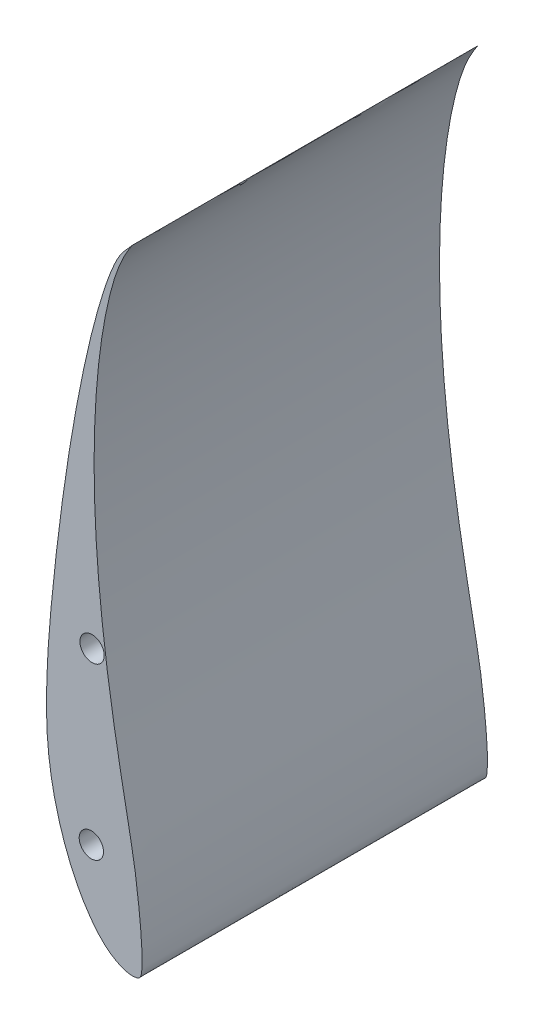
SolidWorks part; units mm, degrees
ref_plane "Front Plane" through (0, 0, 0) normal (0, 0, 1) x (1, 0, 0)
ref_plane "Top Plane" through (0, 0, 0) normal (0, 1, 0) x (1, 0, 0)
ref_plane "Right Plane" through (0, 0, 0) normal (1, 0, 0) x (0, 0, -1)
sketch "Sketch1" plane through (0, 0, 0) normal (0, 0, 1) x (1, 0, 0)
  circle A0 centre (-15.921, -106.9545) radius 5
  circle A1 centre (-15.6291, -36.9545) radius 5
  spline S0 degree 3 poles (0.1447, 113.8075) (0.9877, 115.0494) (0.1764, 113.9605) (-0.5328, 113.2376) (-2.0142, 111.6326) (-3.5901, 109.7391) (-5.1788, 107.1488) (-6.7185, 103.9279) (-8.3253, 100.0394) (-9.9768, 95.4894) (-11.6615, 90.2991) (-13.3647, 84.4953) (-15.0784, 78.1107) (-16.7869, 71.1804) (-18.4777, 63.7441) (-20.1404, 55.8463) (-21.7664, 47.5352) (-23.3357, 38.8592) (-24.846, 29.8731) (-26.2778, 20.6287) (-27.6341, 11.1856) (-28.904, 1.6045) (-30.0835, -8.0452) (-31.1809, -17.6865) (-32.1685, -27.2395) (-33.0279, -36.6264) (-33.7107, -45.7811) (-34.1804, -54.6515) (-34.3832, -63.188) (-34.3616, -71.347) (-33.9621, -79.1133) (-33.1526, -86.4898) (-32.0078, -93.5067) (-30.5249, -100.1655) (-28.7859, -106.4595) (-26.8217, -112.3621) (-24.6782, -117.848) (-22.3669, -122.8833) (-19.9348, -127.4518) (-17.4094, -131.5286) (-14.825, -135.0882) (-12.2364, -138.129) (-9.6154, -140.6071) (-6.9845, -142.5105) (-4.4251, -143.9166) (-1.995, -144.8177) (0.248, -145.2471) (2.145, -145.1642) (3.8849, -144.6758) (4.7485, -142.8604) (4.8697, -140.4195) (4.9872, -137.0804) (4.8061, -132.8812) (4.4733, -127.8694) (3.9403, -122.1008) (3.2191, -115.6344) (2.2943, -108.5018) (1.0016, -100.7063) (-0.6193, -92.2102) (-2.3834, -82.9708) (-4.246, -73.0333) (-6.1298, -62.4603) (-7.9642, -51.3293) (-9.6878, -39.7266) (-11.2375, -27.7523) (-12.5681, -15.5141) (-13.6198, -3.1275) (-14.3654, 9.2832) (-14.7753, 21.5882) (-14.8271, 33.6541) (-14.5172, 45.3463) (-13.853, 56.5309) (-12.8429, 67.0734) (-11.5258, 76.8483) (-9.9399, 85.7283) (-8.1383, 93.6094) (-6.2105, 100.3462) (-4.153, 105.8595) (-2.2701, 109.7932) (-0.5291, 112.6934) (0.1447, 113.8075) (0.9877, 115.0494) (0.1764, 113.9605) knots -0.009748 -0.004147 -0.001 0 0.00098 0.003649 0.007483 0.012095 0.017526 0.024052 0.031783 0.040678 0.05071 0.061833 0.073989 0.087118 0.101145 0.115991 0.13157 0.147788 0.164551 0.181758 0.199312 0.217095 0.23499 0.252857 0.270541 0.287887 0.304773 0.321101 0.336806 0.3518 0.366031 0.379616 0.392653 0.40517 0.417172 0.428604 0.439419 0.449597 0.459102 0.467908 0.475988 0.483309 0.489875 0.495803 0.501149 0.505903 0.510047 0.513579 0.516447 0.51935 0.523823 0.529974 0.537716 0.546968 0.557637 0.56962 0.582804 0.597247 0.613135 0.630444 0.649056 0.668822 0.689595 0.71119 0.733427 0.756094 0.778989 0.80189 0.824567 0.846792 0.868338 0.888978 0.908492 0.926659 0.943286 0.958169 0.971136 0.981956 0.990252 0.995853 0.999 1 1.00098 1.003649 1.007483 only from (0.8199, 114.8137) to (0.8199, 114.8137)
  dimension "D2" = 10
  dimension "D3" = 10
  dimension "D1" = 70
extrude "Boss-Extrude1" add sketch "Sketch1" along normal blind 142
